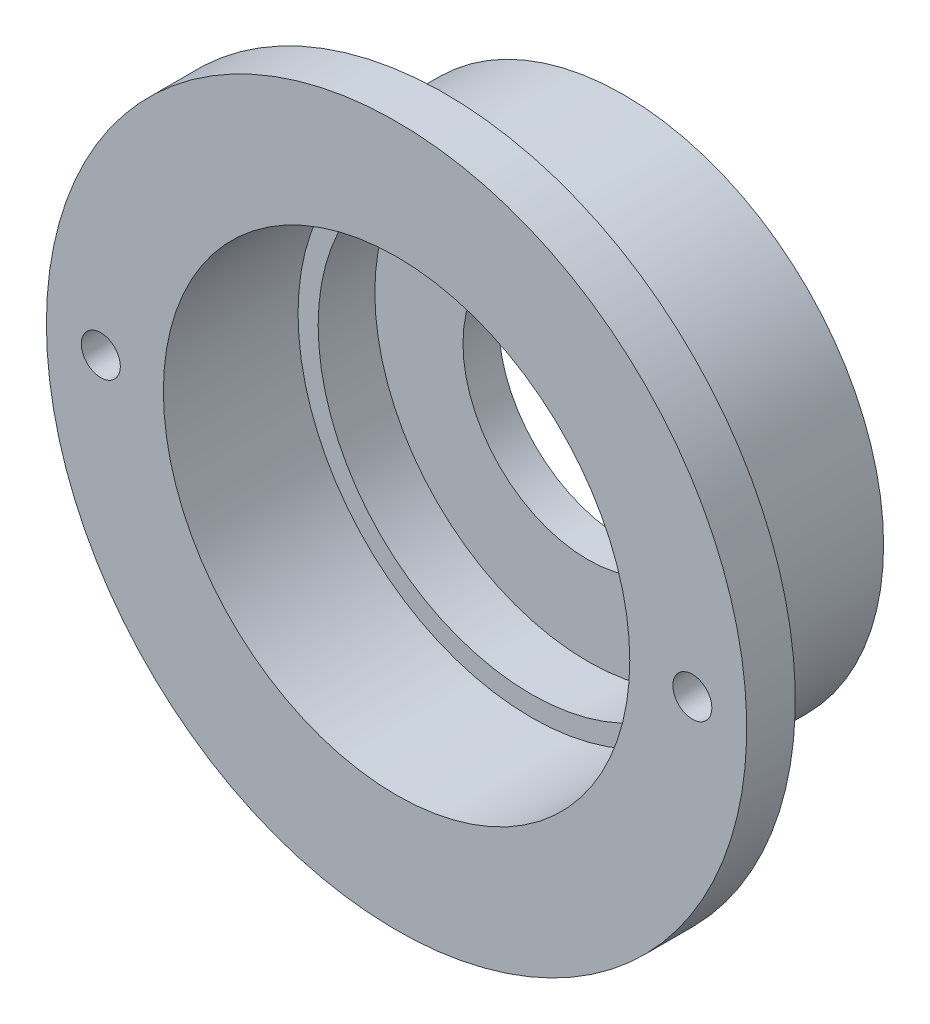
SolidWorks part; units mm, degrees
ref_plane "Front Plane" through (0, 0, 0) normal (0, 0, 1) x (1, 0, 0)
ref_plane "Top Plane" through (0, 0, 0) normal (0, 1, 0) x (1, 0, 0)
ref_plane "Right Plane" through (0, 0, 0) normal (1, 0, 0) x (0, 0, -1)
sketch "Sketch1" plane through (0, 0, 0) normal (0, 1, 0) x (1, 0, 0)
  line L0 (0, 25.4113) -> (0, -24.5124) construction
  line L2 (-7, 4.7005) -> (-19.6178, 4.7005)
  line L3 (-7, 4.7005) -> (-7, 2.7005)
  line L4 (-7, 2.7005) -> (-19.6178, 2.7005)
  line L5 (-19.6178, 4.7005) -> (-19.6178, 2.7005)
  line L6 (-11.938, 2.7005) -> (-19.6178, 2.7005)
  line L7 (-11.938, 2.7005) -> (-11.938, -0.4745)
  line L8 (-11.938, -0.4745) -> (-19.6178, -0.4745)
  line L9 (-19.6178, 2.7005) -> (-19.6178, -0.4745)
  line L10 (-13.0646, -0.4745) -> (-19.6178, -0.4745)
  line L11 (-13.0646, -0.4745) -> (-13.0646, -8.0195)
  line L12 (-13.0646, -8.0195) -> (-19.6178, -8.0195)
  line L13 (-19.6178, -0.4745) -> (-19.6178, -8.0195)
  dimension "D1" = 7
  dimension "D2" = 3.175
  dimension "D3" = 2
  dimension "D4" = 12.72
  dimension "D5" = 11.938
  dimension "D6" = 6.5532
revolve "Revolve1" add sketch "Sketch1" angle 360 about L0
sketch "Sketch2" plane through (0, 0, -4.7005) normal (0, 0, -1) x (-1, 0, 0)
  line L0 (19.6178, 0) -> (-19.6178, 0) construction
  line L1 (0, 19.4384) -> (0, -19.6178) construction
  circle A0 centre (0, 0) radius 19.6178 construction
  circle A1 centre (0, 0) radius 14.565
  circle A2 centre (0, 0) radius 26.6528
  dimension "D1" = 29.13
extrude "Cut-Extrude1" cut sketch "Sketch2" against normal blind 10
sketch "Sketch4" plane through (0, 0, 5.2995) normal (0, 0, -1) x (-1, 0, 0)
  line L0 (19.6178, 0) -> (-19.6178, 0) construction
  line L1 (0, 18.9883) -> (0, -18.5199) construction
  circle A0 centre (0, 0) radius 19.6178 construction
  circle A1 centre (16.57, 0) radius 1.0922
  circle A2 centre (0, 0) radius 14.565 construction
  circle A3 centre (-16.57, 0) radius 1.0922
  point P11 (14.565, 0)
  point P15 (0, 0)
  dimension "D1" = 2.1844
  dimension "D2" = 16.57
extrude "Cut-Extrude2" cut sketch "Sketch4" against normal through all
